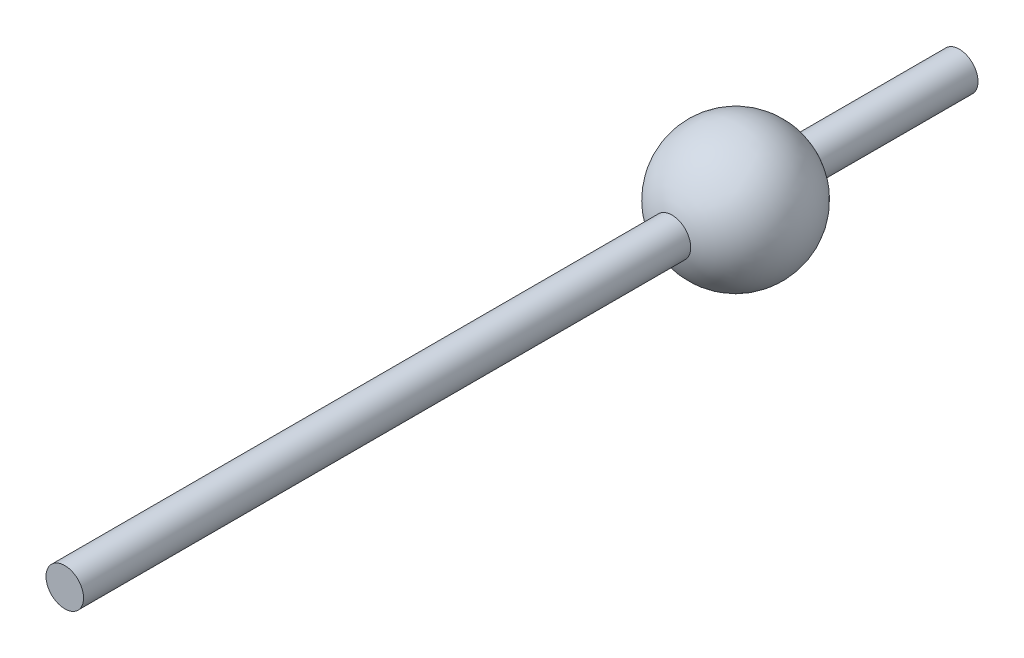
SolidWorks part; units mm, degrees
ref_plane "Front Plane" through (0, 0, 0) normal (0, 0, 1) x (1, 0, 0)
ref_plane "Top Plane" through (0, 0, 0) normal (0, 1, 0) x (1, 0, 0)
ref_plane "Right Plane" through (0, 0, 0) normal (1, 0, 0) x (0, 0, -1)
sketch "Sketch1" plane through (0, 0, 0) normal (0, 0, 1) x (1, 0, 0)
  line L0 (0, 14.85) -> (0, -14.85) construction
  line L1 (0, 14.85) -> (0, -14.85)
  arc A0 (0, -14.85) -> (0, 14.85) centre (0, 0) ccw
  dimension "D1" = 29.7
revolve "Revolve1" add sketch "Sketch1" angle 360 about L1
sketch "Sketch2" plane through (0, 0, 0) normal (0, 0, 1) x (1, 0, 0)
  circle A0 centre (0, 0) radius 4.2
  dimension "D1" = 8.4
extrude "Cut-Extrude1" cut sketch "Sketch2" against normal through all both and the other way through all
sketch "Sketch3" plane through (0, 0, 0) normal (0, 0, 1) x (1, 0, 0)
  circle A0 centre (0, 0) radius 4.2
extrude "Boss-Extrude1" add sketch "Sketch3" along normal mid plane 200
sketch "Sketch4" plane through (0, 0, -100) normal (0, 0, -1) x (-1, 0, 0)
  circle A1 centre (0, 0) radius 4.2
  circle A2 centre (0, 0) radius 4.2
  dimension "D1" = 0
extrude "Cut-Extrude2" cut sketch "Sketch4" against normal blind 50
sketch "Sketch5" plane through (0, 0, 100) normal (0, 0, 1) x (1, 0, 0)
  circle A1 centre (0, 0) radius 4.2
  circle A2 centre (0, 0) radius 4.2
  dimension "D1" = 0
extrude "Boss-Extrude2" add sketch "Sketch5" along normal blind 50
